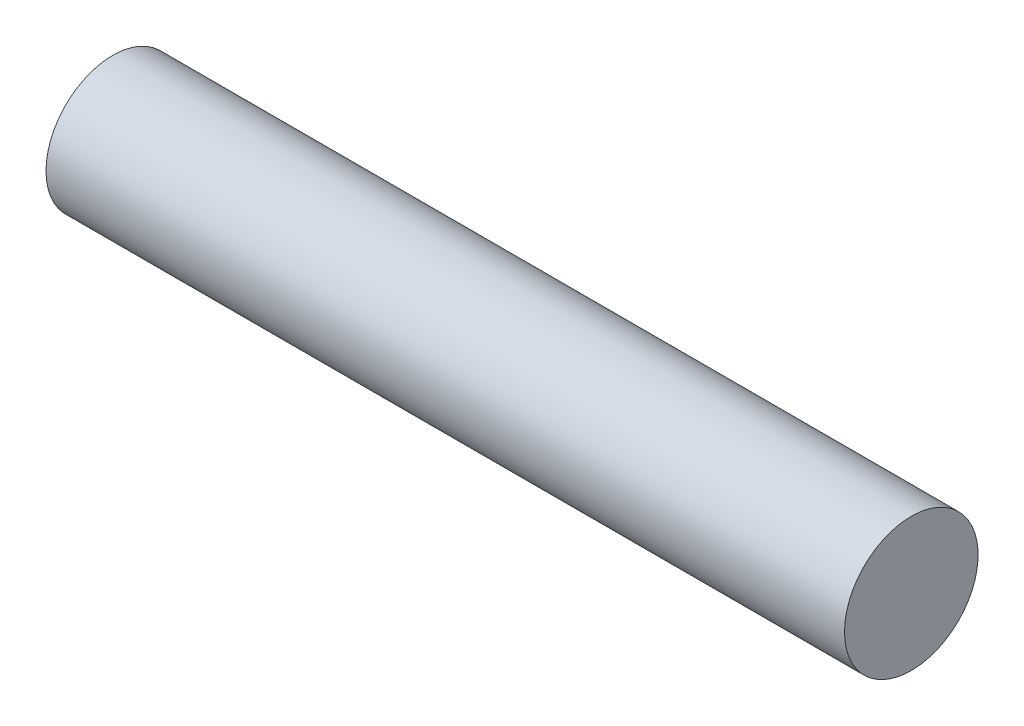
SolidWorks part; units mm, degrees
ref_plane "Front Plane" through (0, 0, 0) normal (0, 0, 1) x (1, 0, 0)
ref_plane "Top Plane" through (0, 0, 0) normal (0, 1, 0) x (1, 0, 0)
ref_plane "Right Plane" through (0, 0, 0) normal (1, 0, 0) x (0, 0, -1)
sketch "Sketch1" plane through (0, 0, 0) normal (1, 0, 0) x (0, 0, -1)
  circle A0 centre (-40.5083, -0.8109) radius 5.08
extrude "Boss-Extrude2" add sketch "Sketch1" along normal blind 60.706 contours A0
